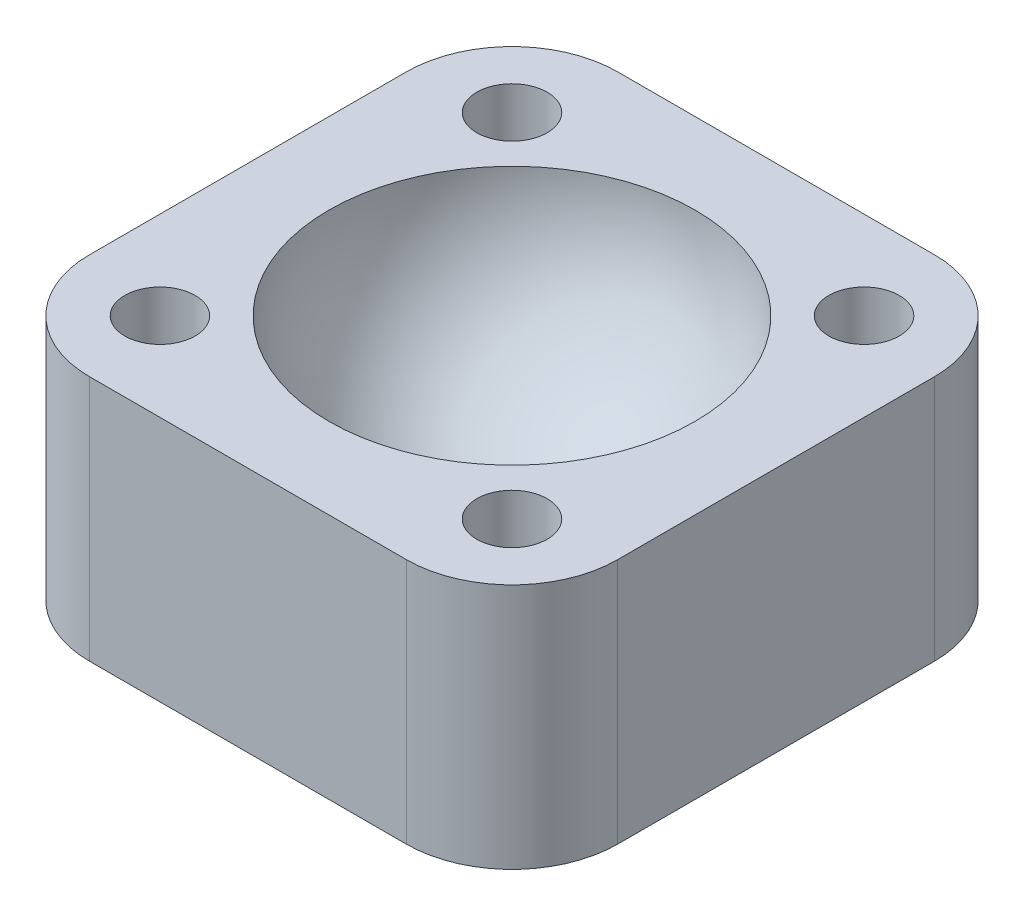
SolidWorks part; units mm, degrees
ref_plane "Front" through (0, 0, 0) normal (0, 0, 1) x (1, 0, 0)
ref_plane "Top" through (0, 0, 0) normal (0, 1, 0) x (1, 0, 0)
ref_plane "Right" through (0, 0, 0) normal (1, 0, 0) x (0, 0, -1)
sketch "Sketch1" plane through (0, 0, 0) normal (0, 1, 0) x (1, 0, 0)
  line L1 (0, 0) -> (15, 0)
  line L2 (0, 0) -> (0, -15)
  line L3 (0, -15) -> (15, -15)
  line L4 (15, 0) -> (15, -15)
  dimension "D1" = 15
  dimension "D2" = 15
extrude "Boss-Extrude1" add sketch "Sketch1" along normal blind 7
sketch "Sketch2" plane through (0, 7, 0) normal (0, 1, 0) x (1, 0, 0)
  line L0 (0, -15) -> (15, -15) construction
  line L1 (15, -15) -> (15, 0) construction
  line L2 (12.7, -7.5) -> (2.3, -7.5)
  arc A0 (2.3, -7.5) -> (12.7, -7.5) centre (7.5, -7.5) ccw
  dimension "D1" = 10.4
  dimension "D2" = 7.5
  dimension "D3" = 7.5
revolve "Cut-Revolve1" cut sketch "Sketch2" angle 360 about L2
sketch "Sketch3" plane through (0, 7, 0) normal (0, 1, 0) x (1, 0, 0)
  line L0 (0, -15) -> (15, -15) construction
  line L1 (0, 0) -> (0, -15) construction
  circle A0 centre (2.5, -12.5) radius 1
  circle A1 centre (12.5, -12.5) radius 1
  circle A2 centre (12.5, -2.5) radius 1
  circle A3 centre (2.5, -2.5) radius 1
  dimension "D1" = 2
  dimension "D2" = 2.5
  dimension "D3" = 2.5
  dimension "D4" = 2
  dimension "D5" = 2
extrude "Cut-Extrude1" cut sketch "Sketch3" against normal through all
fillet "Fillet1" radius 3 4 edges at (15, 3.5, 0) (0, 3.5, 0) (15, 3.5, 15) (0, 3.5, 15)
